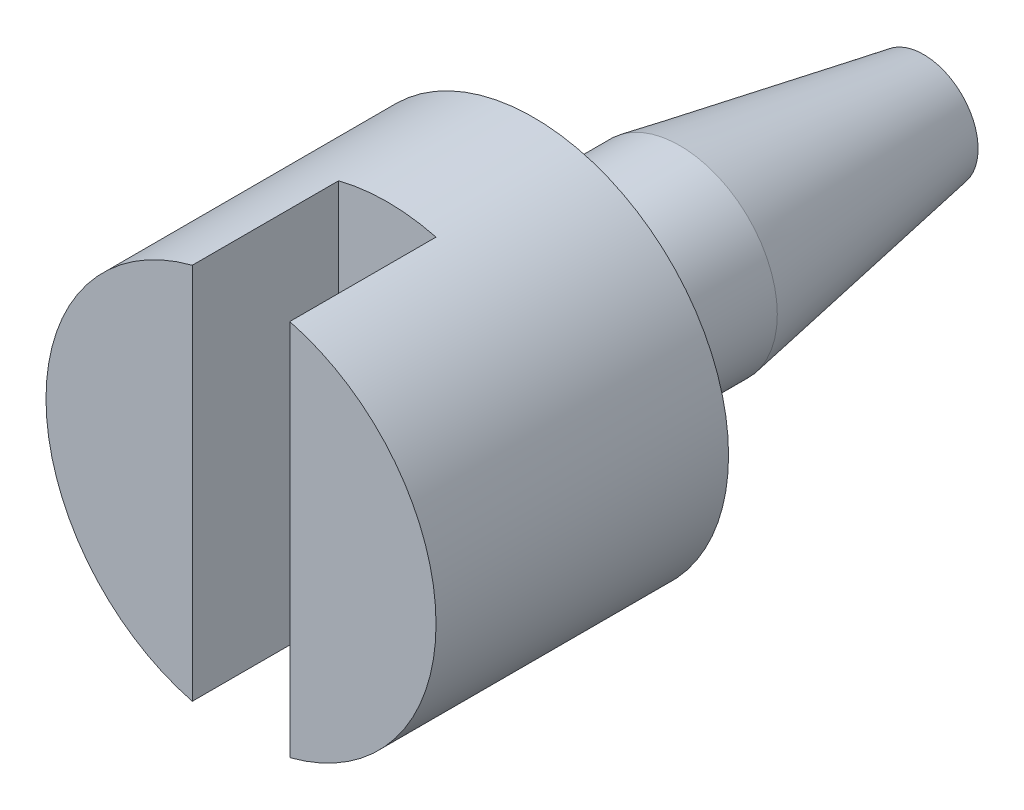
SolidWorks part; units mm, degrees
ref_plane "Face" through (0, 0, 0) normal (0, 0, 1) x (1, 0, 0)
ref_plane "Dessus" through (0, 0, 0) normal (0, 1, 0) x (1, 0, 0)
ref_plane "Droite" through (0, 0, 0) normal (1, 0, 0) x (0, 0, -1)
sketch "Esquisse1" plane through (0, 0, 0) normal (0, 0, 1) x (1, 0, 0)
  circle A0 centre (0, 0) radius 2
  dimension "D1" = 4
extrude "Base-Extrusion" add sketch "Esquisse1" along normal blind 3
sketch "Esquisse2" plane through (0, 0, 0) normal (0, 0, -1) x (-1, 0, 0)
  circle A0 centre (0, 0) radius 1
  dimension "D1" = 2
extrude "Boss.-Extru.1" add sketch "Esquisse2" along normal blind 4
chamfer "Chanfrein2" distance 2.5 angle 10 1 edges at (-1, 0, -4)
sketch "Esquisse3" plane through (0, 0, 3) normal (0, 0, 1) x (1, 0, 0)
  line L0 (0, 2.2614) -> (0, -2.4287)
extrude "Enlèv. de mat.-Extru.-Mince1" cut sketch "Esquisse3" against normal blind 1.5 flip side to cut thin thin type mid plane wall 1
